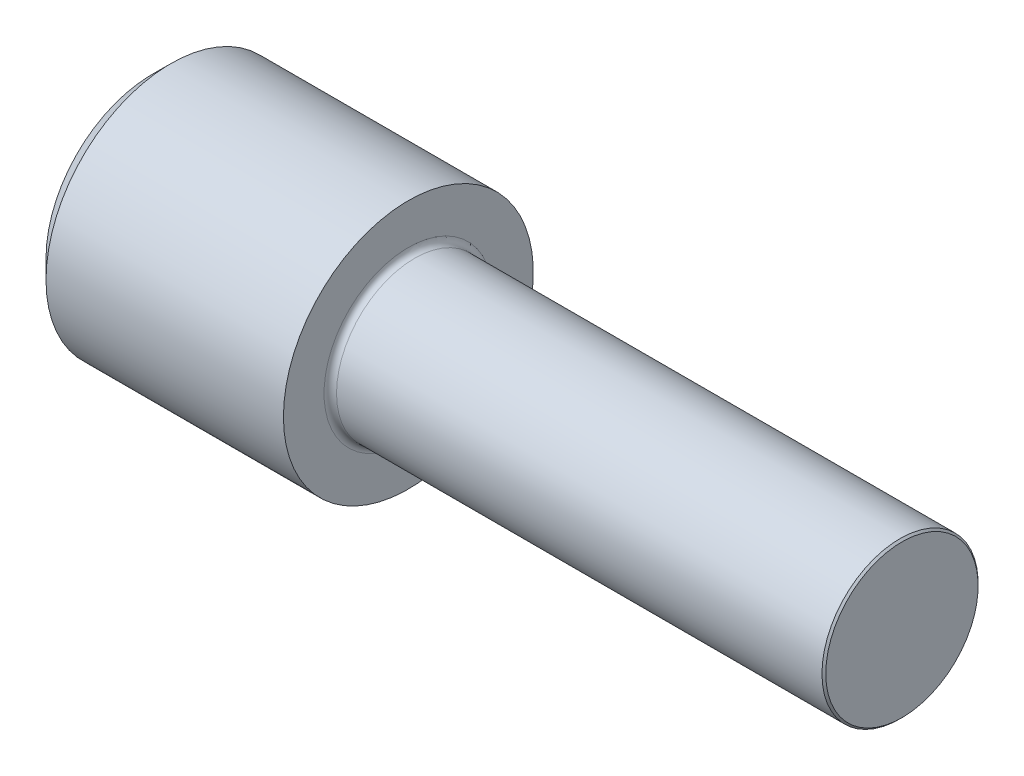
SolidWorks part; units mm, degrees
revolve "Base-Revolve" add sketch "BodySke"
sketch "BodySke" plane through (0, 0, 0) normal (0, 0, 1) x (1, 0, 0)
  line L0 (0, 0) -> (0, 1.7)
  line L1 (0.3, 2) -> (4.1, 2)
  line L2 (4.1, 2) -> (4.1, 1.25)
  line L3 (4.1, 1.25) -> (11.9695, 1.25)
  line L4 (12, 1.2195) -> (12, 0)
  line L5 (12, 0) -> (0, 0)
  line L6 (-31.75, 0) -> (127, 0) construction
  line L7 (0, 1.7) -> (0.3, 2)
  line L8 (12, 1.2195) -> (11.9695, 1.25)
  line L9 (0, -1.7) -> (0.3, -2) construction
  line L10 (12, -1.2195) -> (11.9695, -1.25) construction
  line L11 (4.6, 9.525) -> (4.6, 3.175) construction
  line L12 (7, 9.525) -> (7, 3.175) construction
  line L13 (-38, 9.525) -> (-38, 3.175) construction
  dimension "Diameter" = 2.5
  dimension "Head_ht" = 4.1
  dimension "Length" = 7.9
  dimension "Body_ch_ang" = 45
  dimension "Head_dia" = 4
  dimension "Head_ch_ang" = 45
  dimension "Minor_dia" = 2.439
  dimension "Advance" = 0.5
  dimension "Thread_nom" = 5
  dimension "Thread_length" = 50
  dimension "Head_ch_ht" = 0.3
cosmetic thread "ThreadCosmetic" [suppressed]
fillet "Fillet1" radius 0.1 1 edges at (4.1, 0, 1.25)
ref_plane "Plane1" through (0, 0, 0) normal (0, 0, 1) x (1, 0, 0)
ref_plane "Plane2" through (0, 0, 0) normal (0, 1, 0) x (1, 0, 0)
ref_plane "Plane3" through (0, 0, 0) normal (1, 0, 0) x (0, 0, -1)
sketch "Sketch2" plane through (0, 0, 0) normal (0, 0, 1) x (1, 0, 0)
  line L0 (0, 1.28) -> (1.3, 1.28)
  line L1 (1.3, 1.28) -> (2.039, 0)
  line L2 (-31.75, 0) -> (127, 0) construction
  line L3 (2.039, 0) -> (0, 0)
  line L4 (0, 0) -> (0, 1.28)
  line L5 (0, 1.7) -> (0, -1.7) construction
  line L6 (0, 0) -> (47.625, 0) construction
  line L7 (4.1, -2) -> (4.1, 2) construction
  dimension "D1" = 1.28
  dimension "D2" = 60
revolve "Hex-PreBroach" cut sketch "Sketch2" angle 360 about L6
sketch "Sketch3" plane through (0, 0, 0) normal (-1, 0, 0) x (0, 0.5, 0.866)
  line L0 (0.739, 1.28) -> (-0.739, 1.28)
  line L1 (-0.739, 1.28) -> (-1.478, 0)
  line L2 (0.739, 1.28) -> (1.478, 0)
  line L3 (0.739, -1.28) -> (1.478, 0)
  line L4 (0.739, -1.28) -> (-0.739, -1.28)
  line L5 (-0.739, -1.28) -> (-1.478, 0)
  dimension "D1" = 1.28
  dimension "D2" = 1.28
  dimension "Hex_size" = 2.56
extrude "Hex" cut sketch "Sketch3" against normal blind 1.3
sketch "Sketch4" plane through (0, 0, 0) normal (-1, 0, 0) x (0, 0, 1)
  line L0 (0, 0) -> (1.4605, 0)
  line L1 (0, 0) -> (6.1484, 3.5498) construction
  line L2 (0, 0) -> (0.7302, 1.2648)
  line L3 (1.2009, 0.3267) -> (1.3933, 0.4378)
  line L4 (0.8834, 0.8767) -> (1.0758, 0.9877)
  arc A0 (1.2009, 0.3267) -> (0.8834, 0.8767) centre (0, 0) ccw
  arc A1 (1.4605, 0) -> (1.3933, 0.4378) centre (0, 0) ccw
  arc A2 (0.7302, 1.2648) -> (1.0758, 0.9877) centre (0, 0) cw
  dimension "D1" = 30
  dimension "D2" = 60
  dimension "Spline_p_dim" = 0.635
  dimension "D3" = 0.3175
extrude "Spline" [suppressed] cut sketch "Sketch4" against normal blind 1.3
pattern_circular "CirPattern1" [suppressed] count 6 every 60
sketch "Sketch5" plane through (0, 0, 0) normal (0, 0, 1) x (1, 0, 0)
  line L0 (-31.75, 0) -> (127, 0) construction
  line L2 (0, 1.7) -> (0, -1.7) construction
  circle A0 centre (1.2, 0) radius 0.475
  dimension "Drilled_hole_dia" = 0.95
  dimension "Drilled_hole_loc" = 1.2
extrude "Hole" [suppressed] cut sketch "Sketch5" against normal through all and the other way through all
pattern_circular "Drilled-4" [suppressed] count 2 every 60
pattern_circular "Drilled-6" [suppressed] count 3 every 60
sketch "ThdSchSke" plane through (0, 0, 0) normal (0, 0, 1) x (1, 0, 0)
  line L0 (7, -1.2195) -> (6.9786, -1.25)
  line L1 (7, -1.2195) -> (7.0214, -1.25)
  line L2 (7.0214, -1.25) -> (7.0214, -1.5625)
  line L3 (-3.175, 0) -> (5.1513, 0) construction
  line L5 (7.0214, -1.5625) -> (6.9786, -1.5625)
  line L6 (6.9786, -1.5625) -> (6.9786, -1.25)
  line L7 (0, 1.7) -> (0, -1.7) construction
  dimension "Thread_minor" = 2.439
  dimension "Diameter" = 2.5
  dimension "Start" = 7
revolve "ThreadSchematic" [suppressed] cut sketch "ThdSchSke" angle 360 about L3
pattern_linear "ThdSchPat" [suppressed]
equation "\"D2@Sketch3\" = \"Hex_size@Sketch3\" / 2"
equation "\"D1@Sketch3\" = \"Hex_size@Sketch3\" / 2"
equation "\"D1@Sketch2\" = \"Hex_size@Sketch3\" / 2"
equation "\"D3@Sketch4\" = \"Spline_p_dim@Sketch4\" / 2"
equation "\"Thread_minor@ThreadCosmetic\"  =  \"Minor_dia@BodySke\""
equation "\"D2@CirPattern1\" = 360 / \"Num_teeth@CirPattern1\""
equation "\"Wall_thickness@Sketch2\" = \"Head_ht@BodySke\" - \"Key_eng@Hex\""
equation "\"Thread_length@ThreadCosmetic\" = ((sgn( (\"Length@BodySke\" - \"Advance@BodySke\" ) - \"Thread_nom@BodySke\" )-1)*( (\"Length@BodySke\" - \"Advance@BodySke\" ) - \"Thread_nom@BodySke\" ))/-2+ \"Thread_nom@BodySke\""
equation "\"Thread_minor@ThdSchSke\" = \"Minor_dia@BodySke\""
equation "\"Diameter@ThdSchSke\" = \"Diameter@BodySke\""
equation "\"Overcut@ThdSchSke\" = \"Diameter@BodySke\" * 1.25"
equation "\"Start@ThdSchSke\" = \"Head_ht@BodySke\" + \"Length@BodySke\" - \"Thread_length@ThreadCosmetic\"  '---Non-countersunk---"
equation "\"Num_threads@ThdSchPat\" = int( \"Thread_length@ThreadCosmetic\" / \"Advance@BodySke\" + 0.999 )  + 1"
equation "\"Advance@ThdSchPat\" = \"Thread_length@ThreadCosmetic\" /  (\"Num_threads@ThdSchPat\" - 1) 'relax it"
equation "\"Num_threads@ThdSchPat\" = \"Num_threads@ThdSchPat\" - sgn( \"Num_threads@ThdSchPat\" - 1) '---chamfered tips only---"
